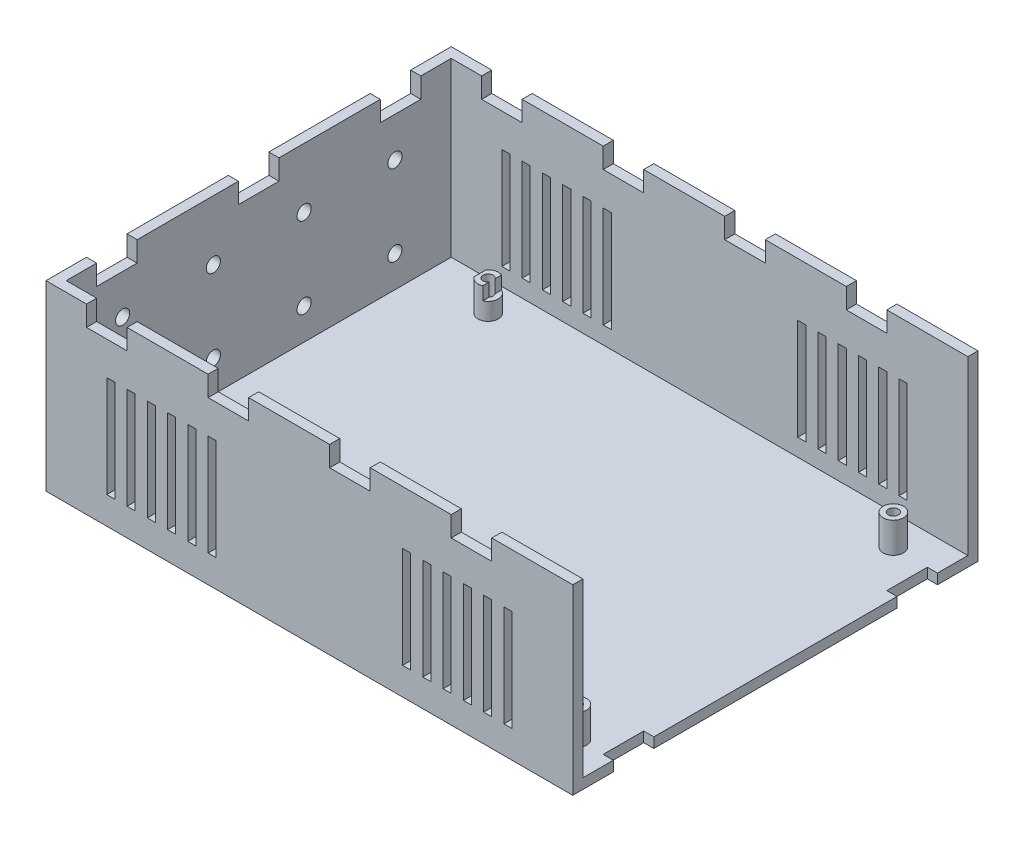
SolidWorks part; units mm, degrees
ref_plane "Front Plane" through (0, 0, 0) normal (0, 0, 1) x (1, 0, 0)
ref_plane "Top Plane" through (0, 0, 0) normal (0, 1, 0) x (1, 0, 0)
ref_plane "Right Plane" through (0, 0, 0) normal (1, 0, 0) x (0, 0, -1)
sketch "Sketch1" plane through (0, 0, 0) normal (0, 1, 0) x (1, 0, 0)
  line L1 (65, -50) -> (-65, -50)
  line L2 (65, -50) -> (65, 50)
  line L3 (65, 50) -> (-65, 50)
  line L4 (-65, -50) -> (-65, 50)
  line L5 (65, -50) -> (-65, 50) construction
  line L6 (65, 50) -> (-65, -50) construction
  point P0 (0, 0)
  dimension "D1" = 100
  dimension "D2" = 130
extrude "Boss-Extrude2" add sketch "Sketch1" along normal blind 45
sketch "Sketch2" plane through (0, 45, 0) normal (0, 1, 0) x (1, 0, 0)
  line L0 (-65, 50) -> (-65, -50) construction
  line L1 (-62.5, -47.5) -> (62.5, -47.5)
  line L2 (-62.5, -47.5) -> (-62.5, 47.5)
  line L3 (-62.5, 47.5) -> (62.5, 47.5)
  line L4 (62.5, -47.5) -> (62.5, 47.5)
  line L5 (-62.5, -47.5) -> (62.5, 47.5) construction
  line L6 (-62.5, 47.5) -> (62.5, -47.5) construction
  line L7 (65, 50) -> (-65, 50) construction
  point P0 (0, 0)
  dimension "D1" = 2.5
  dimension "D2" = 2.5
extrude "Cut-Extrude2" cut sketch "Sketch2" against normal blind 42.5
sketch "Sketch3" plane through (65, 0, 0) normal (1, 0, 0) x (0, 0, -1)
  line L0 (-50, 45) -> (-50, 0) construction
  line L1 (47.5, 2.5) -> (-47.5, 2.5)
  line L2 (47.5, 2.5) -> (47.5, 45)
  line L3 (47.5, 45) -> (-47.5, 45)
  line L4 (-47.5, 2.5) -> (-47.5, 45)
  line L5 (47.5, 2.5) -> (-47.5, 45) construction
  line L6 (47.5, 45) -> (-47.5, 2.5) construction
  line L7 (50, 45) -> (50, 0) construction
  line L8 (-50, 0) -> (50, 0) construction
  line L9 (-50, 45) -> (50, 45) construction
  point P0 (0, 23.75)
  dimension "D1" = 2.5
  dimension "D2" = 2.5
  dimension "D3" = 2.5
  dimension "D4" = 0
extrude "Cut-Extrude3" cut sketch "Sketch3" against normal blind 30
sketch "Sketch4" plane through (0, 0, 50) normal (0, 0, 1) x (1, 0, 0)
  line L0 (-65, 45) -> (65, 45) construction
  line L1 (-55, 45) -> (-45, 45)
  line L2 (-55, 45) -> (-55, 40)
  line L3 (-55, 40) -> (-45, 40)
  line L4 (-45, 45) -> (-45, 40)
  line L5 (-65, 45) -> (-65, 0) construction
  dimension "D1" = 10
  dimension "D2" = 5
  dimension "D3" = 10
extrude "Cut-Extrude4" cut sketch "Sketch4" against normal through all contours L2 L1 L4 L3
pattern_linear "LPattern1" count 4 spacing 30 along (1, 0, 0) of "Cut-Extrude4"
sketch "Sketch5" plane through (-65, 0, 0) normal (-1, 0, 0) x (0, 0, 1)
  line L0 (-50, 45) -> (50, 45) construction
  line L1 (-40, 45) -> (-30, 45)
  line L2 (-40, 45) -> (-40, 40)
  line L3 (-40, 40) -> (-30, 40)
  line L4 (-30, 45) -> (-30, 40)
  line L5 (-50, 45) -> (-50, 0) construction
  dimension "D1" = 10
  dimension "D2" = 5
  dimension "D3" = 10
extrude "Cut-Extrude5" cut sketch "Sketch5" against normal through all contours L2 L1 L4 L3
pattern_linear "LPattern2" count 3 spacing 35 along (0, 0, 1) of "Cut-Extrude5"
sketch "Sketch6" plane through (0, 0, 0) normal (0, -1, 0) x (1, 0, 0)
  line L0 (-65, -50) -> (-65, 50) construction
  line L1 (65, -50) -> (-65, -50) construction
  line L2 (-65, 50) -> (65, 50) construction
  line L3 (65, 50) -> (65, -50) construction
  circle A0 centre (-46, -40.1) radius 2.5
  circle A1 centre (-46, 40.1) radius 2.5
  circle A2 centre (56, 40.1) radius 2.5
  circle A3 centre (54, -40.1) radius 2.5
  dimension "D1" = 5
  dimension "D2" = 19
  dimension "D3" = 9.9
  dimension "D4" = 5
  dimension "0.5cm" = 5
  dimension "D5" = 5
  dimension "D6" = 9.9
  dimension "D7" = 9.9
  dimension "D8" = 19
  dimension "D9" = 9
  dimension "D10" = 11
  dimension "0.99cm" = 9.9
extrude "Boss-Extrude6" add sketch "Sketch6" against normal blind 10
sketch "Sketch8" plane through (0, 10, 0) normal (0, 1, 0) x (1, 0, 0)
  circle A0 centre (56, -40.1) radius 1.25
  circle A1 centre (54, 40.1) radius 1.25
  circle A2 centre (-46, 40.1) radius 1.25
  circle A3 centre (-46, -40.1) radius 1.25
  dimension "D1" = 2.5
  dimension "D2" = 2.5
  dimension "D3" = 2.5
  dimension "D4" = 2.5
extrude "Cut-Extrude8" cut sketch "Sketch8" against normal blind 7.5
sketch "Sketch10" plane through (-65, 0, 0) normal (-1, 0, 0) x (0, 0, 1)
  line L0 (-50, 45) -> (-50, 0) construction
  line L1 (-40, 40) -> (-30, 40) construction
  circle A2 centre (-33.6, 10.25) radius 1.75
  circle A3 centre (-33.6, 30.25) radius 1.75
  dimension "D5" = 3.5
  dimension "D6" = 3.5
  dimension "D7" = 20
  dimension "D8" = 16.4
  dimension "D9" = 9.75
extrude "Cut-Extrude10" cut sketch "Sketch10" against normal blind 2.5
pattern_linear "LPattern3" count 4 spacing 22.4 along (0, 0, 1) of "Cut-Extrude10"
sketch "Sketch11" plane through (65, 0, 0) normal (1, 0, 0) x (0, 0, -1)
  line L0 (-50, 0) -> (50, 0) construction
  line L1 (-40, 0) -> (-30, 0)
  line L2 (-40, 0) -> (-40, 2.5)
  line L3 (-40, 2.5) -> (-30, 2.5)
  line L4 (-30, 0) -> (-30, 2.5)
  line L5 (-47.5, 2.5) -> (47.5, 2.5) construction
  line L6 (-50, 45) -> (-50, 0) construction
  dimension "D1" = 10
  dimension "D2" = 10
extrude "Cut-Extrude11" cut sketch "Sketch11" against normal blind 2.5
sketch "Sketch12" plane through (65, 0, 0) normal (1, 0, 0) x (0, 0, -1)
  line L0 (-30, 0) -> (50, 0) construction
  line L1 (40, 0) -> (30, 0)
  line L2 (40, 0) -> (40, 2.5)
  line L3 (40, 2.5) -> (30, 2.5)
  line L4 (30, 0) -> (30, 2.5)
  line L5 (47.5, 2.5) -> (-47.5, 2.5) construction
  line L6 (50, 45) -> (50, 0) construction
  dimension "D1" = 10
  dimension "D2" = 10
extrude "Cut-Extrude12" cut sketch "Sketch12" against normal blind 2.5
sketch "Sketch13" plane through (0, 0, -50) normal (0, 0, -1) x (-1, 0, 0)
  line L0 (-65, 45) -> (-65, 0) construction
  line L1 (-50, 31.7795) -> (-48, 31.7795)
  line L2 (-50, 31.7795) -> (-50, 6.7795)
  line L3 (-50, 6.7795) -> (-48, 6.7795)
  line L4 (-48, 31.7795) -> (-48, 6.7795)
  dimension "D1" = 2
  dimension "D2" = 25
  dimension "D3" = 15
extrude "Cut-Extrude13" cut sketch "Sketch13" against normal through all
pattern_linear "LPattern4" count 6 spacing 5 along (-1, 0, 0) of "Cut-Extrude13"
mirror "Mirror1" about plane through (0, 0, 0) normal (1, 0, 0) of "LPattern4", "Cut-Extrude13"
